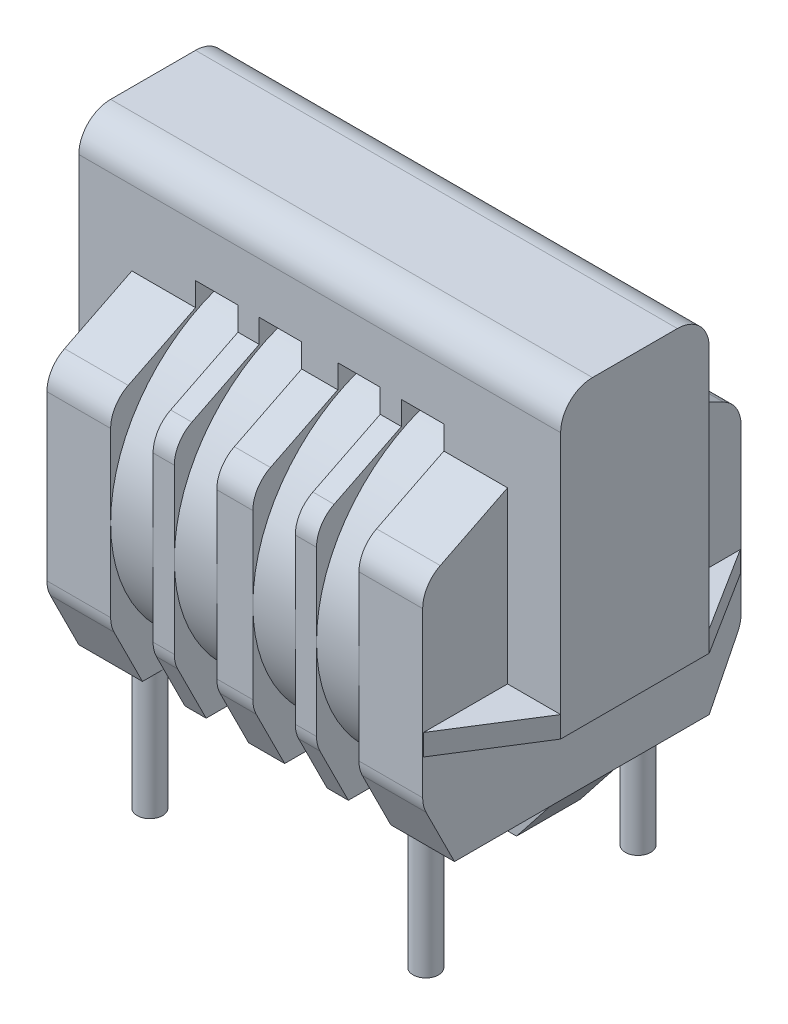
SolidWorks part; units mm, degrees
material "Ст3пс ГОСТ 380-2005"
ref_plane "Спереди" through (0, 0, 0) normal (0, 0, 1) x (1, 0, 0)
ref_plane "Сверху" through (0, 0, 0) normal (0, 1, 0) x (1, 0, 0)
ref_plane "Справа" through (0, 0, 0) normal (1, 0, 0) x (0, 0, -1)
sketch "Эскиз1" plane through (0, 0, 0) normal (1, 0, 0) x (0, 0, -1)
  line L0 (-7.5, 2.5) -> (-3.5, 4.5)
  line L2 (-7.5, 2.5) -> (-7.5, -6.5)
  line L3 (-7.5, -9.5) -> (7.5, -9.5) construction
  line L4 (7.5, 2.5) -> (7.5, -6.5)
  line L5 (0, -9.5) -> (0, 9.5) construction
  line L6 (-7.5, 0) -> (7.5, 0) construction
  line L7 (3.5, 9.5) -> (-3.5, 9.5)
  line L8 (3.5, 9.5) -> (3.5, 4.5)
  line L9 (3.5, 4.5) -> (-3.5, 4.5) construction
  line L10 (-3.5, 9.5) -> (-3.5, 4.5)
  line L11 (0, 4.5) -> (0, 9.5) construction
  line L12 (3.5, 7) -> (-3.5, 7) construction
  line L13 (3.5, 4.5) -> (7.5, 2.5)
  line L14 (-6, -9.5) -> (-7.5, -6.5)
  line L15 (-6, -9.5) -> (6, -9.5)
  line L16 (6, -9.5) -> (7.5, -6.5)
  point P0 (0, 0)
  point P154 (0, 7)
  dimension "D1" = 15
  dimension "D2" = 19
  dimension "D3" = 7
  dimension "D4" = 5
  dimension "D5" = 12
  dimension "D6" = 3
  dimension "D7" = 12
extrude "Бобышка-Вытянуть1" add sketch "Эскиз1" along normal blind 17.7
fillet "Скругление1" radius 1.5 6 edges at (8.85, 9.5, 3.5) (8.85, 9.5, -3.5) (8.85, 2.5, 7.5) (8.85, 2.5, -7.5) (8.85, -6.5, -7.5) (8.85, -6.5, 7.5)
sketch "Эскиз2" plane through (0, 0, 0) normal (-1, 0, 0) x (0, 0, 1)
  line L0 (3.5, 8) -> (3.5, 4.5) construction
  line L1 (-2, 9.5) -> (2, 9.5) construction
  line L2 (-3.5, 4.5) -> (-3.5, 8) construction
  line L3 (3.5, 8) -> (3.5, 4.5) construction
  line L4 (-2, 9.5) -> (2, 9.5) construction
  line L5 (-3.5, 4.5) -> (-3.5, 8) construction
  line L7 (-2, 9.5) -> (2, 9.5)
  line L8 (-3.5, 8) -> (-3.5, -4.5)
  line L9 (-3.5, -4.5) -> (3.5, -4.5)
  line L10 (3.5, 8) -> (3.5, -4.5)
  line L11 (0, -4.5) -> (0, 9.5) construction
  line L12 (-3.5, 2.5) -> (3.5, 2.5) construction
  arc A0 (3.5, 8) -> (2, 9.5) centre (2, 8) ccw construction
  arc A1 (-2, 9.5) -> (-3.5, 8) centre (-2, 8) ccw construction
  arc A2 (3.5, 8) -> (2, 9.5) centre (2, 8) ccw
  arc A3 (-2, 9.5) -> (-3.5, 8) centre (-2, 8) ccw
  point P146 (0, 2.5)
  dimension "D1" = 14
  dimension "D2" = 7
  dimension "D3" = 2.5
extrude "Бобышка-Вытянуть2" add sketch "Эскиз2" along normal blind 2.5 and the other way blind 20.2
sketch "Эскиз4" plane through (0, -4.5, 0) normal (0, -1, 0) x (1, 0, 0)
  line L0 (0, 3.5) -> (-2.5, 3.5) construction
  line L1 (0, 3.5) -> (-2.5, 3.5)
  line L2 (0, 3.5) -> (0, 7.4648)
  line L3 (-2.5, 3.5) -> (0, 7.4648)
extrude "Бобышка-Вытянуть3" add sketch "Эскиз4" against normal blind 1
mirror "Зеркальное отражение4" about plane through (0, 0, 0) normal (0, 0, 1) of "Бобышка-Вытянуть3"
ref_plane "Плоскость5" through (8.85, 0, 0) normal (-1, 0, 0) x (0, 0, 1)
mirror "Зеркальное отражение6" about plane through (8.85, 0, 0) normal (-1, 0, 0) of "Зеркальное отражение4", "Бобышка-Вытянуть3"
sketch "Эскиз5" plane through (0, -9.5, 0) normal (0, -1, 0) x (1, 0, 0)
  line L0 (17.7, 6) -> (17.7, -6) construction
  line L1 (17.7, 6) -> (17.7, -6) construction
  line L2 (0, 0) -> (17.7, 0) construction
  line L4 (2.35, 5) -> (15.35, 5) construction
  line L5 (2.35, 5) -> (2.35, -5) construction
  line L6 (2.35, -5) -> (15.35, -5) construction
  line L7 (15.35, 5) -> (15.35, -5) construction
  line L8 (8.85, -5) -> (8.85, 5) construction
  line L9 (2.35, 0) -> (15.35, 0) construction
  circle A0 centre (2.35, 5) radius 0.6
  circle A1 centre (15.35, 5) radius 0.6
  circle A2 centre (15.35, -5) radius 0.6
  circle A3 centre (2.35, -5) radius 0.6
  point P5 (8.85, 0)
  dimension "D3" = 1.2
  dimension "D1" = 13
  dimension "D2" = 10
extrude "Бобышка-Вытянуть4" add sketch "Эскиз5" along normal blind 6
sketch "Эскиз8" plane through (0, 0, 0) normal (0, 0, 1) x (1, 0, 0)
  line L0 (17.7, -9.5) -> (0, -9.5) construction
  line L1 (2, -9.5) -> (0, -9.5)
  line L2 (2, -9.5) -> (2, -11.5)
  line L3 (2, -11.5) -> (1.5773, -11.5)
  line L4 (1.5773, -11.5) -> (0, -9.5)
  dimension "D1" = 2
  dimension "D2" = 2
extrude "Бобышка-Вытянуть6" add sketch "Эскиз8" along normal blind 1.5 and the other way blind 1.5
mirror "Зеркальное отражение7" about plane through (8.85, 0, 0) normal (-1, 0, 0) of "Бобышка-Вытянуть6"
ref_plane "Плоскость6" through (3, 0, 0) normal (-1, 0, 0) x (0, 0, 1)
sketch "Эскиз9" plane through (3, 0, 0) normal (-1, 0, 0) x (0, 0, 1)
  line L0 (7.5, 1.5729) -> (7.5, -6.1459) construction
  line L1 (-7.5, -6.1459) -> (-7.5, 1.5729) construction
  line L2 (7.5, 1.5729) -> (7.5, -6.1459) construction
  line L3 (-7.5, -6.1459) -> (-7.5, 1.5729) construction
  line L4 (-7.5, -2.2865) -> (7.5, -2.2865) construction
  line L5 (-6.6708, 2.9146) -> (-3.5, 4.5) construction
  line L6 (-6.6708, 2.9146) -> (-3.5, 4.5) construction
  line L7 (-3.5, 4.5) -> (3.6706, 4.5) construction
  line L8 (-1.5, -9.5) -> (-6, -9.5) construction
  line L9 (-4.7447, -9.5) -> (-6, -9.5)
  line L10 (-6, -9.5) -> (-7.3416, -6.8167) construction
  line L11 (-6, -9.5) -> (-7.3071, -6.8857)
  line L12 (7.3416, -6.8167) -> (6, -9.5) construction
  line L13 (6, -9.5) -> (1.5, -9.5) construction
  line L14 (7.3071, -6.8857) -> (6, -9.5)
  line L15 (6, -9.5) -> (4.7447, -9.5)
  arc A1 (-6.6708, 2.9146) -> (-7.5, 1.5729) centre (-6, 1.5729) ccw construction
  arc A2 (-6.6708, 2.9146) -> (-7.5, 1.5729) centre (-6, 1.5729) ccw construction
  arc A3 (-4.7447, -9.5) -> (4.7447, -9.5) centre (0, -2.2865) ccw
  circle A4 centre (0, -2.2865) radius 7.5
  arc A5 (7.3071, -6.8857) -> (-7.3071, -6.8857) centre (0, -2.2865) ccw
extrude "Вырез-Вытянуть1" cut sketch "Эскиз9" against normal blind 2
pattern_linear "Линейный массив1" count 2 spacing 3 along (1, 0, 0) of "Вырез-Вытянуть1"
mirror "Зеркальное отражение8" about plane through (8.85, 0, 0) normal (-1, 0, 0) of "Линейный массив1", "Вырез-Вытянуть1"
